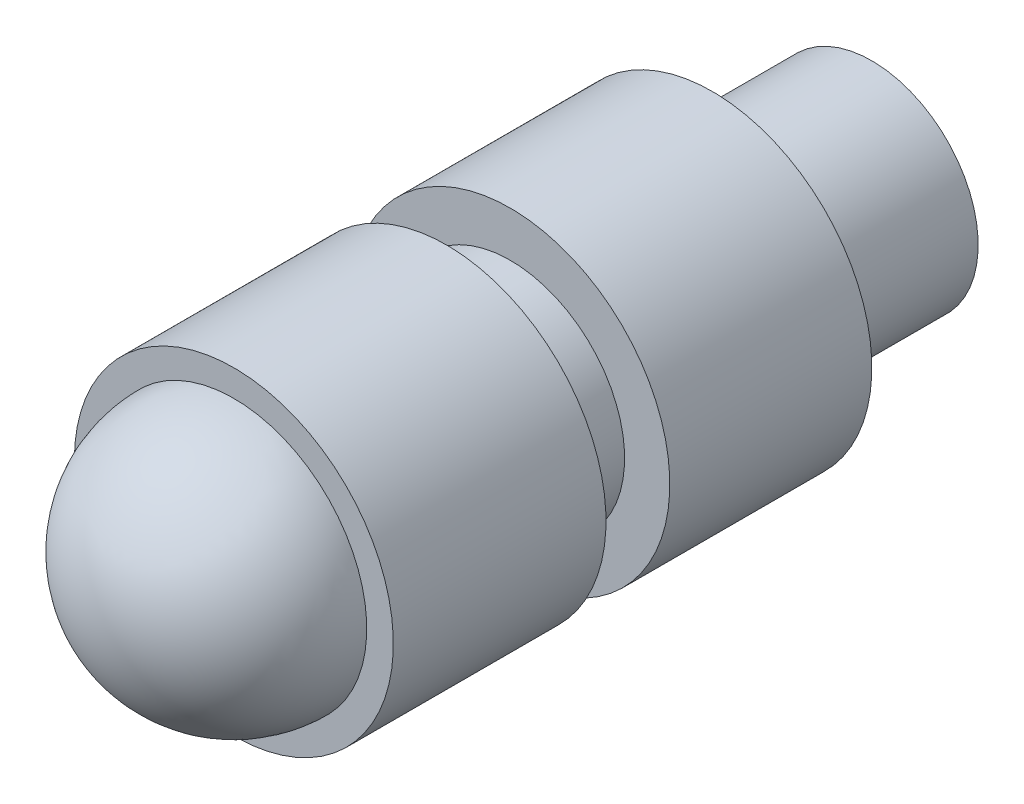
SolidWorks part; units mm, degrees
ref_plane "前视基准面" through (0, 0, 0) normal (0, 0, 1) x (1, 0, 0)
ref_plane "上视基准面" through (0, 0, 0) normal (0, 1, 0) x (1, 0, 0)
ref_plane "右视基准面" through (0, 0, 0) normal (1, 0, 0) x (0, 0, -1)
other "Configuration Table"
sketch "草图1" plane through (0, 0, 0) normal (0, 1, 0) x (1, 0, 0)
  line L0 (0, 30) -> (0, -10) construction
  line L1 (5, 0) -> (6, 0)
  line L2 (6, 0) -> (6, 8)
  line L3 (6, 8) -> (4.3, 8)
  line L4 (4.3, 8) -> (4.3, 10.4)
  line L5 (4.3, 10.4) -> (6, 10.4)
  line L6 (6, 10.4) -> (6, 18)
  line L7 (6, 18) -> (4, 18)
  line L8 (4, 18) -> (4, 24)
  line L9 (4, 24) -> (0, 24)
  line L10 (0, 24) -> (0, -5)
  arc A0 (0, -5) -> (5, 0) centre (-0.0001, 0.0001) ccw
revolve "旋转1" add sketch "草图1" angle 360 about L0
